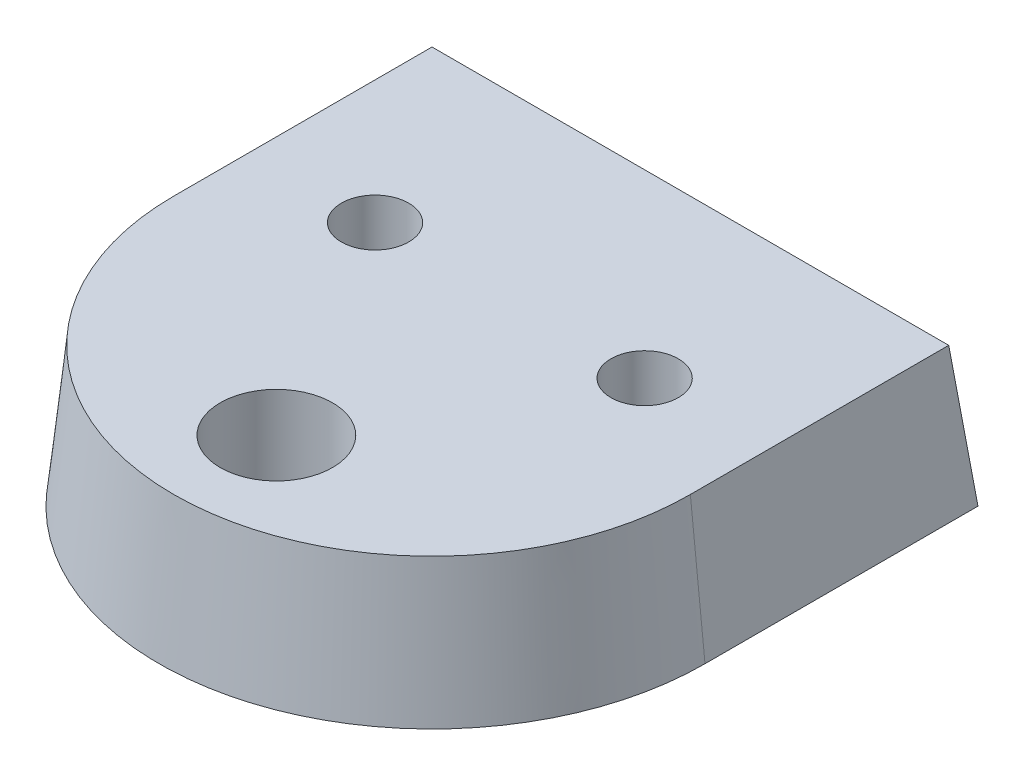
SolidWorks part; units mm, degrees
ref_plane "Front Plane" through (0, 0, 0) normal (0, 0, 1) x (1, 0, 0)
ref_plane "Top Plane" through (0, 0, 0) normal (0, 1, 0) x (1, 0, 0)
ref_plane "Right Plane" through (0, 0, 0) normal (1, 0, 0) x (0, 0, -1)
sketch "Sketch1" plane through (0, 0, 0) normal (0, 1, 0) x (1, 0, 0)
  line L0 (-11.5, 11.5) -> (11.5, 11.5)
  line L1 (11.5, 11.5) -> (11.5, 0)
  line L2 (-11.5, 11.5) -> (-11.5, 0)
  arc A0 (-11.5, 0) -> (11.5, 0) centre (0, 0) ccw
  point P5 (-11.5, 14.2726)
  dimension "D1" = 23
extrude "Boss-Extrude1" add sketch "Sketch1" against normal blind 6.2 draft 6 draft outward yes
sketch "Sketch2" plane through (0, 0, 0) normal (0, 1, 0) x (1, 0, 0)
  line L0 (-6, 3.4641) -> (6, 3.4641) construction
  line L1 (6, 3.4641) -> (0, -6.9282) construction
  line L2 (0, -6.9282) -> (-6, 3.4641) construction
  line L3 (0, 0) -> (0, 8.9573) construction
  line L4 (-4.4858, 0) -> (5.8244, 0) construction
  line L5 (-6, 3.4641) -> (3, -1.7321) construction
  circle A0 centre (-6, 3.4641) radius 1.5
  circle A1 centre (6, 3.4641) radius 1.5
  circle A2 centre (0, -6.9282) radius 2.5
  point P11 (0, 0)
  dimension "D3" = 3
  dimension "D4" = 5
  dimension "D1" = 12
  dimension "D2" = 12
extrude "Cut-Extrude1" cut sketch "Sketch2" against normal through all
shell "Shell1" thickness 1.2
